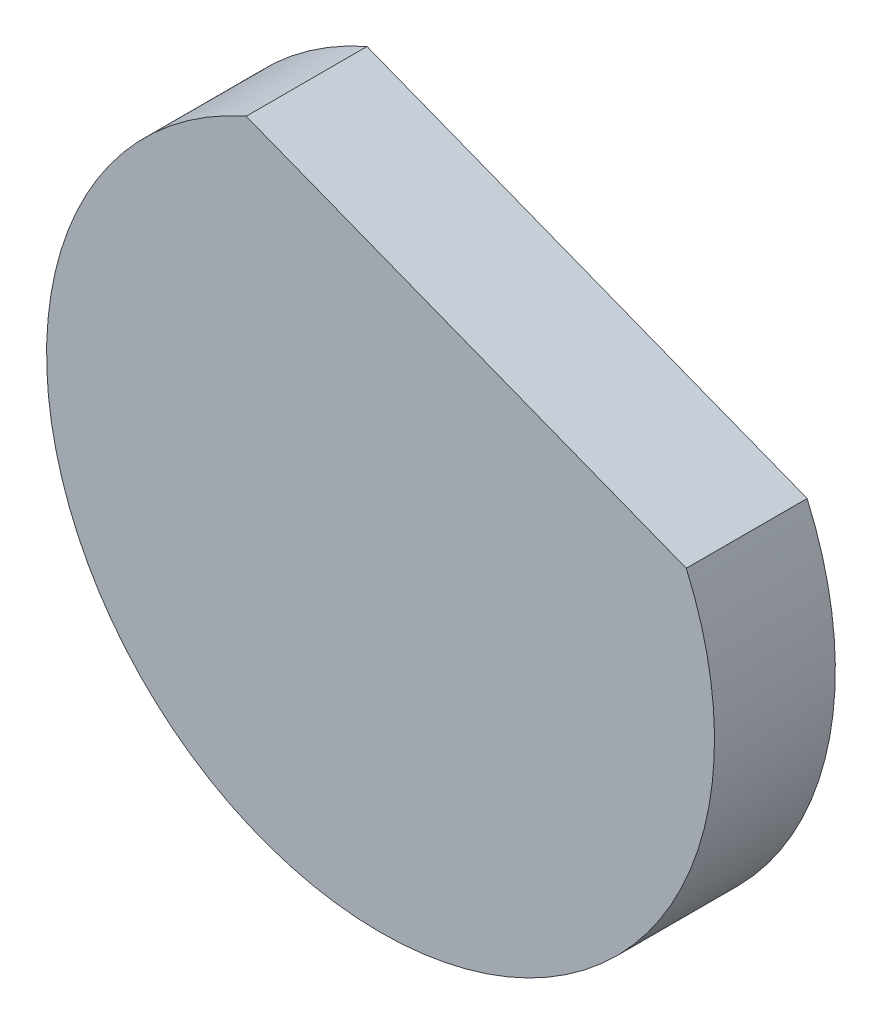
SolidWorks part; units mm, degrees
ref_plane "Front Plane" through (0, 0, 0) normal (0, 0, 1) x (1, 0, 0)
ref_plane "Top Plane" through (0, 0, 0) normal (0, 1, 0) x (1, 0, 0)
ref_plane "Right Plane" through (0, 0, 0) normal (1, 0, 0) x (0, 0, -1)
sketch "CurveSketch" plane through (0, 0, 0) normal (0, 0, 1) x (1, 0, 0)
  line L0 (-13.0738, 31.7833) -> (12.9273, 21.6558)
  arc A0 (12.9273, 21.6558) -> (-13.0738, 31.7833) centre (-5.137, 13.719) cw
  dimension "D1" = 19.731
extrude "CurveBoss" add sketch "CurveSketch" along normal blind 7.139
